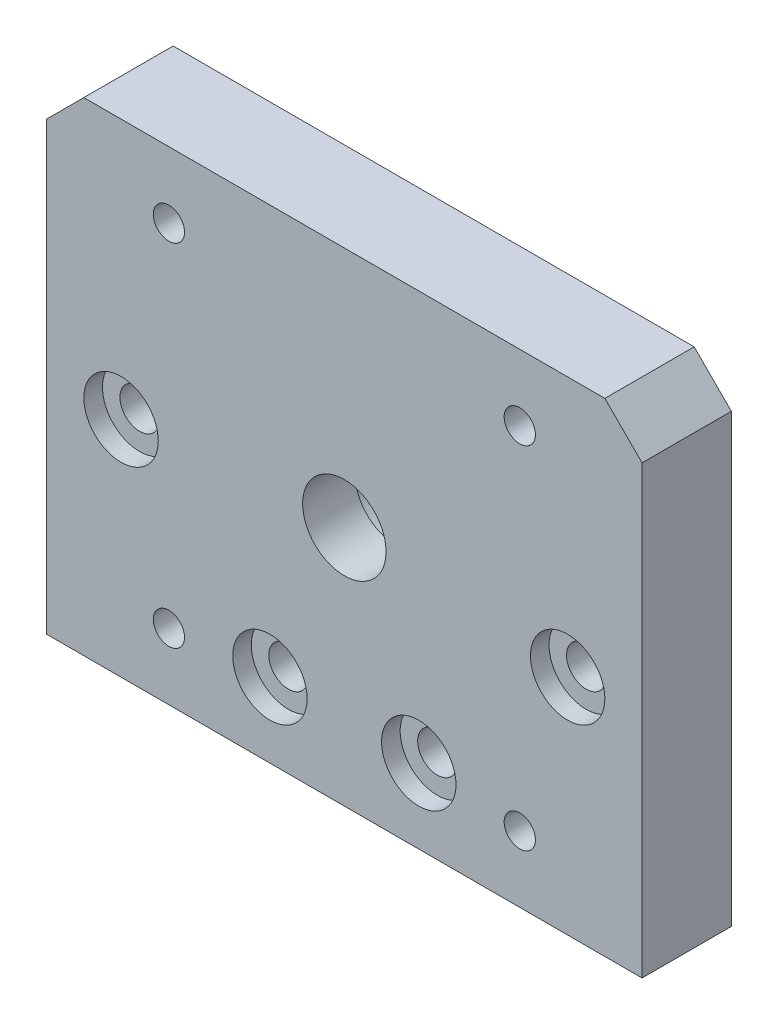
SolidWorks part; units mm, degrees
ref_plane "Front" through (0, 0, 0) normal (0, 0, 1) x (1, 0, 0)
ref_plane "Top" through (0, 0, 0) normal (0, 1, 0) x (1, 0, 0)
ref_plane "Right" through (0, 0, 0) normal (1, 0, 0) x (0, 0, -1)
sketch "Sketch1" plane through (0, 0, 0) normal (0, 0, 1) x (1, 0, 0)
  line L0 (-40, 17.6) -> (-40, -32.4)
  line L1 (-40, -32.4) -> (40, -32.4)
  line L2 (40, -32.4) -> (40, 17.6)
  line L3 (40, 17.6) -> (-40, 17.6)
  point P0 (-30, -2.4)
  point P1 (0, 0)
  point P2 (30, -2.4)
  point P3 (23.57, -23.5)
  point P4 (10, -22.4)
  point P5 (-10, -22.4)
  point P6 (-23.57, -23.5)
  point P11 (23.57, 23.64)
  point P13 (0, 0)
  point P14 (0, 0)
  point P15 (0, 0)
  point P17 (-23.57, 23.64)
  dimension "D1" = 17.6
  dimension "D2" = 32.4
  dimension "D3" = 40
  dimension "D4" = 80
  dimension "D5" = 60
  dimension "D6" = 2.4
  dimension "D7" = 30
  dimension "D8" = 10
  dimension "D9" = 20
  dimension "D10" = 22.4
  dimension "D11" = 23.5
  dimension "D12" = 23.57
  dimension "D13" = 47.14
  dimension "D14" = 47.14
sketch "Sketch3" plane through (0, 0, 0) normal (0, 0, 1) x (1, 0, 0)
  line L0 (40, -32.4) -> (40, 17.6) construction
  line L1 (-40, -32.4) -> (40, -32.4)
  line L2 (-40, -32.4) -> (-40, 27.54)
  line L3 (-35, 32.54) -> (35, 32.54)
  line L4 (40, -32.4) -> (40, 27.54)
  line L5 (-40, 27.54) -> (-35, 32.54)
  line L6 (35, 32.54) -> (40, 27.54)
  point P1 (40, 32.54)
  point P2 (-40, 32.54)
  dimension "D1" = 8.9
extrude "Boss-Extrude1" add sketch "Sketch3" along normal blind 12
hole_wizard "M5 Tapped Hole1" positions "Sketch4" profile "Sketch5" tap size "M5" standard "ISO" end condition through all
sketch "Sketch4" plane through (0, 0, 12) normal (0, 0, 1) x (1, 0, 0)
  point P0 (-23.57, -23.5)
  point P3 (-23.57, 23.64)
  point P6 (23.57, 23.64)
  point P9 (23.57, -23.5)
sketch "Sketch5" plane through (-23.57, -23.5, 12) normal (1, 0, 0) x (0, -1, 0)
  line L0 (0, 0) -> (0, 12)
  line L1 (0, 12) -> (2.1, 12)
  line L2 (2.1, 12) -> (2.1, 0)
  line L5 (2.1, 0) -> (0, 0)
  line L11 (0, -6.35) -> (0, 107.95) construction
  dimension "Thru Tap Drill Dia." = 4.2
  dimension "Thru Tap Drill Depth" = 12
cosmetic thread "Hole Thread1" parameters "D2"=5
cosmetic thread "Hole Thread2" parameters "D2"=5
cosmetic thread "Hole Thread3" parameters "D2"=5
cosmetic thread "Hole Thread4" parameters "D2"=5
hole_wizard "CBORE for M5 Hex Socket Head Cap Screw1" positions "Sketch6" profile "Sketch7" counterbore size "M5" standard "ISO" end condition through all
sketch "Sketch6" plane through (0, 0, 12) normal (0, 0, 1) x (1, 0, 0)
  point P0 (-30, -2.4)
  point P3 (-10, -22.4)
  point P6 (10, -22.4)
  point P9 (30, -2.4)
sketch "Sketch7" plane through (-30, -2.4, 12) normal (1, 0, 0) x (0, -1, 0)
  line L0 (0, 0) -> (0, 12)
  line L1 (0, 12) -> (2.65, 12)
  line L3 (2.65, 12) -> (2.65, 2.5)
  line L4 (2.65, 2.5) -> (5, 2.5)
  line L5 (5, 2.5) -> (5, 0)
  line L7 (5, 0) -> (0, 0)
  line L11 (0, -6.35) -> (0, 107.95) construction
  dimension "Thru Hole Dia." = 5.3
  dimension "Thru Hole Depth" = 12
  dimension "C'Bore Dia." = 10
  dimension "C'Bore Depth" = 2.5
sketch "Sketch8" plane through (0, 0, 12) normal (0, 0, 1) x (1, 0, 0)
  circle A0 centre (0, 0) radius 5.6
  dimension "D1" = 11.2
extrude "Cut-Extrude1" cut sketch "Sketch8" against normal blind 12
sketch "Sketch9" plane through (0, 0, 0) normal (0, 0, -1) x (-1, 0, 0)
  circle A0 centre (0, 0) radius 8
  dimension "D1" = 16
extrude "Cut-Extrude2" cut sketch "Sketch9" against normal blind 5
